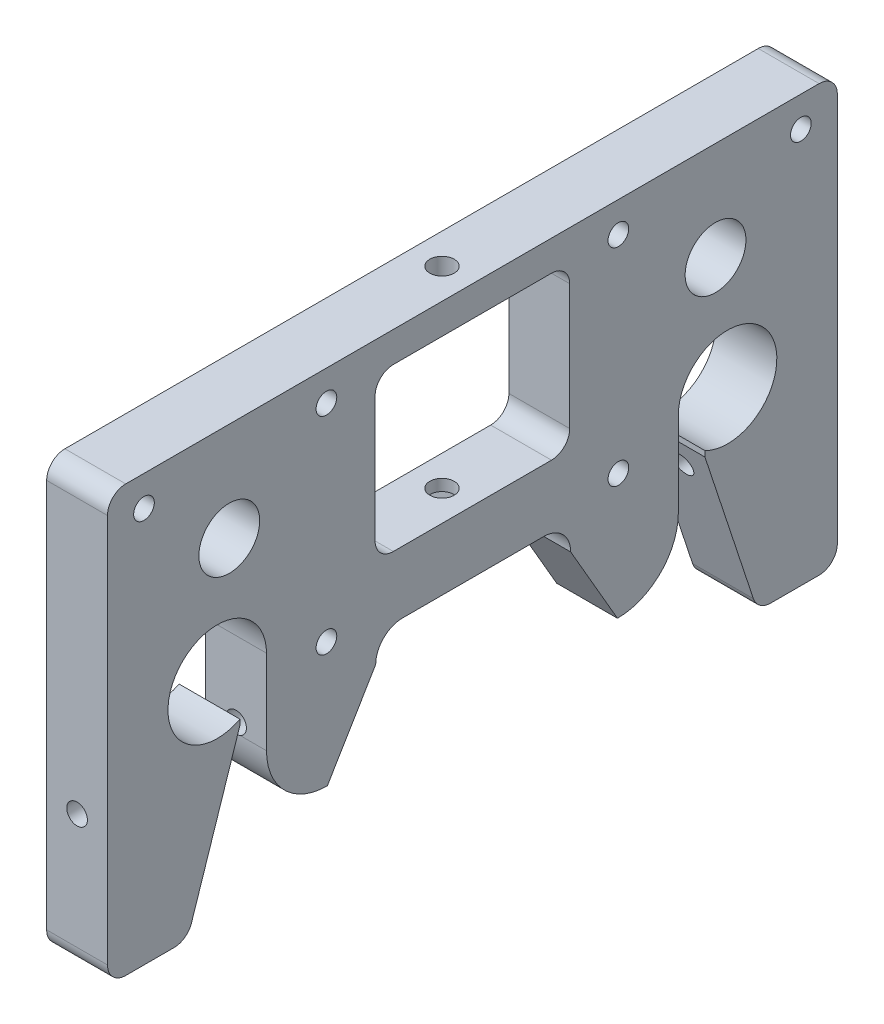
SolidWorks part; units mm, degrees
ref_plane "Спереди" through (0, 0, 0) normal (0, 0, 1) x (1, 0, 0)
ref_plane "Сверху" through (0, 0, 0) normal (0, 1, 0) x (1, 0, 0)
ref_plane "Справа" through (0, 0, 0) normal (1, 0, 0) x (0, 0, -1)
sketch "Эскиз1" plane through (0, 0, 0) normal (1, 0, 0) x (0, 0, -1)
  line L0 (3, 0) -> (10.9531, 0)
  line L1 (120, 3) -> (120, 67)
  line L2 (117, 70) -> (3, 70)
  line L3 (0, 67) -> (0, 3)
  line L4 (0, 0) -> (0, 34.4099)
  line L5 (42, 65) -> (36, 65)
  line L6 (21.7669, 26.2099) -> (13.8022, 2.0604)
  line L7 (21.7669, 26.2099) -> (21.7669, 27.1263)
  line L8 (26.1459, 34.3209) -> (26.1458, 20.4331)
  line L9 (60, -930) -> (60, 49070)
  line L10 (36.1458, 10.433) -> (83.8542, 10.433)
  line L11 (47, 65) -> (73, 65)
  line L12 (93.8541, 34.3209) -> (93.8542, 20.4331)
  line L13 (36, 65) -> (36, 31)
  line L14 (36, 31) -> (36, 65)
  line L15 (98.2331, 26.2099) -> (98.2331, 27.1263)
  line L16 (47, 38.3803) -> (73, 38.3803)
  line L17 (36, 65) -> (6, 65)
  line L18 (42, 65) -> (44, 65)
  line L19 (44, 62) -> (44, 41.3803)
  line L20 (98.2331, 26.2099) -> (106.1978, 2.0604)
  line L21 (76, 62) -> (76, 41.3803)
  line L22 (84, 65) -> (114, 65)
  line L23 (109.0469, 0) -> (117, 0)
  line L24 (48.5129, 23.732) -> (71.7456, 23.732) construction
  line L25 (48.5129, 28.1481) -> (71.7456, 28.1481)
  line L26 (48.5129, 19.3158) -> (71.7456, 19.3158)
  arc A0 (26.1459, 34.3209) -> (21.7669, 27.1263) centre (18.0459, 34.321) ccw
  circle A1 centre (36, 65) radius 1.7
  circle A2 centre (6, 65) radius 1.7
  circle A3 centre (36, 31) radius 1.7
  arc A4 (93.8541, 34.3209) -> (98.2331, 27.1263) centre (101.9541, 34.321) cw
  circle A5 centre (84, 31) radius 1.7
  circle A6 centre (84, 65) radius 1.7
  circle A7 centre (114, 65) radius 1.7
  arc A8 (26.1458, 20.4331) -> (36.1458, 10.433) centre (36.1458, 20.433) ccw
  arc A9 (93.8542, 20.4331) -> (83.8542, 10.433) centre (83.8542, 20.433) cw
  arc A10 (44, 62) -> (47, 65) centre (47, 62) cw
  arc A11 (76, 41.3803) -> (73, 38.3803) centre (73, 41.3803) cw
  arc A12 (76, 62) -> (73, 65) centre (73, 62) ccw
  arc A13 (44, 41.3803) -> (47, 38.3803) centre (47, 41.3803) ccw
  arc A14 (3, 70) -> (0, 67) centre (3, 67) ccw
  arc A15 (120, 3) -> (117, 0) centre (117, 3) cw
  arc A16 (0, 3) -> (3, 0) centre (3, 3) ccw
  arc A17 (120, 67) -> (117, 70) centre (117, 67) ccw
  arc A18 (106.1978, 2.0604) -> (109.0469, 0) centre (109.0469, 3) ccw
  arc A19 (13.8022, 2.0604) -> (10.9531, 0) centre (10.9531, 3) cw
  arc A20 (48.5129, 28.1481) -> (48.5129, 19.3158) centre (48.5129, 23.732) ccw
  arc A21 (71.7456, 19.3158) -> (71.7456, 28.1481) centre (71.7456, 23.732) ccw
  point P16 (60, 70)
  point P22 (60, 10.433)
  point P36 (60, 38.3803)
  point P37 (60, 65)
  point P43 (26.1456, 10.433)
  point P46 (93.8544, 10.433)
  point P52 (76, 38.3803)
  point P55 (76, 65)
  point P58 (44, 38.3803)
  point P70 (106.8774, 0)
  point P73 (13.1226, 0)
  point P76 (60.1293, 23.732)
  dimension "D1" = 10
  dimension "D2" = 3
  dimension "D3" = 3
  dimension "D4" = 3
  dimension "D5" = 3
extrude "Бобышка-Вытянуть1" add sketch "Эскиз1" along normal blind 10
sketch "Эскиз2" plane through (0, 70, 0) normal (0, 1, 0) x (1, 0, 0)
  line L0 (5, 120) -> (5, 60)
  line L1 (10, 120) -> (0, 120) construction
  line L2 (5, 60) -> (9.6374, 60)
  circle A0 centre (5, 60) radius 2
extrude "Вырез-Вытянуть1" cut sketch "Эскиз2" against normal blind 37 contours L0 A0 L2 | L2 A0 L0
sketch "Эскиз3" plane through (0, 0, 0) normal (-1, 0, 0) x (0, 0, 1)
  line L0 (-89.4771, 22) -> (-89.4771, 24.8977)
  line L2 (-89.4771, 22) -> (-89.4771, 19.1)
  line L3 (-62.9206, 34.9875) -> (-62.9206, 36.4951)
  line L5 (-62.9206, 36.4951) -> (-57.116, 36.4951)
  line L6 (-57.116, 36.4951) -> (-57.116, 33.4799)
  line L7 (-57.116, 33.4799) -> (-62.9206, 33.4799)
  line L8 (-62.9206, 33.4799) -> (-62.9206, 35.0855)
  line L11 (-89.4771, 22) -> (-87.9771, 22)
  line L12 (-87.9771, 22) -> (-87.9771, 24.8926)
  line L13 (-87.9771, 24.8926) -> (-87.9771, 19.0972)
  line L14 (-87.9771, 19.0972) -> (-90.9771, 19.0972)
  line L15 (-90.9771, 19.0972) -> (-90.9771, 24.8926)
  line L16 (-90.9771, 24.8926) -> (-87.9771, 24.8926)
  line L18 (-32.0229, 24.8922) -> (-32.0229, 19.099)
  line L19 (-32.0229, 19.099) -> (-29.0229, 19.099)
  line L20 (-29.0229, 24.8922) -> (-32.0229, 24.8922)
  line L21 (-29.0229, 19.099) -> (-29.0229, 24.8922)
  point P1 (0, 0)
  point P3 (0, 0)
  point P14 (-60.0183, 34.9875)
  point P21 (-30.5229, 21.9956)
extrude "Вырез-Вытянуть2" cut sketch "Эскиз3" against normal blind 8
sketch "Эскиз5" plane through (0, 0, -120) normal (0, 0, -1) x (-1, 0, 0)
  line L0 (-5, 70) -> (-5, 22)
  line L1 (-10, 70) -> (0, 70) construction
  circle A0 centre (-5, 22) radius 1.7
extrude "Вырез-Вытянуть3" cut sketch "Эскиз5" against normal blind 35
sketch "Эскиз6" plane through (0, 0, 0) normal (0, 0, 1) x (1, 0, 0)
  line L0 (5, 70) -> (5, 22)
  line L1 (10, 70) -> (0, 70) construction
  circle A0 centre (5, 22) radius 1.7
extrude "Вырез-Вытянуть4" cut sketch "Эскиз6" against normal blind 35
sketch "Эскиз7" plane through (0, 0, 0) normal (-1, 0, 0) x (0, 0, 1)
  line L0 (-76.1617, 23.732) -> (-83.8542, 10.433)
  line L1 (-83.8542, 10.433) -> (-36.1458, 10.433)
  line L2 (-36.1458, 10.433) -> (-44.0968, 23.732)
  line L3 (-76.1617, 23.732) -> (-44.0968, 23.732)
  arc A0 (-71.7456, 28.1481) -> (-71.7456, 19.3158) centre (-71.7456, 23.732) ccw construction
  arc A1 (-48.5129, 19.3158) -> (-48.5129, 28.1481) centre (-48.5129, 23.732) ccw construction
extrude "Вырез-Вытянуть5" cut sketch "Эскиз7" against normal blind 10
sketch "Эскиз9" plane through (0, 0, 0) normal (-1, 0, 0) x (0, 0, 1)
  line L0 (-60, 70) -> (-60, 31.9679)
  line L1 (-117, 70) -> (-3, 70) construction
  circle A0 centre (-99.974, 53.7494) radius 5
  circle A1 centre (-20.026, 53.7494) radius 5
extrude "Вырез-Вытянуть6" cut sketch "Эскиз9" against normal blind 10 contours A0 | A1
